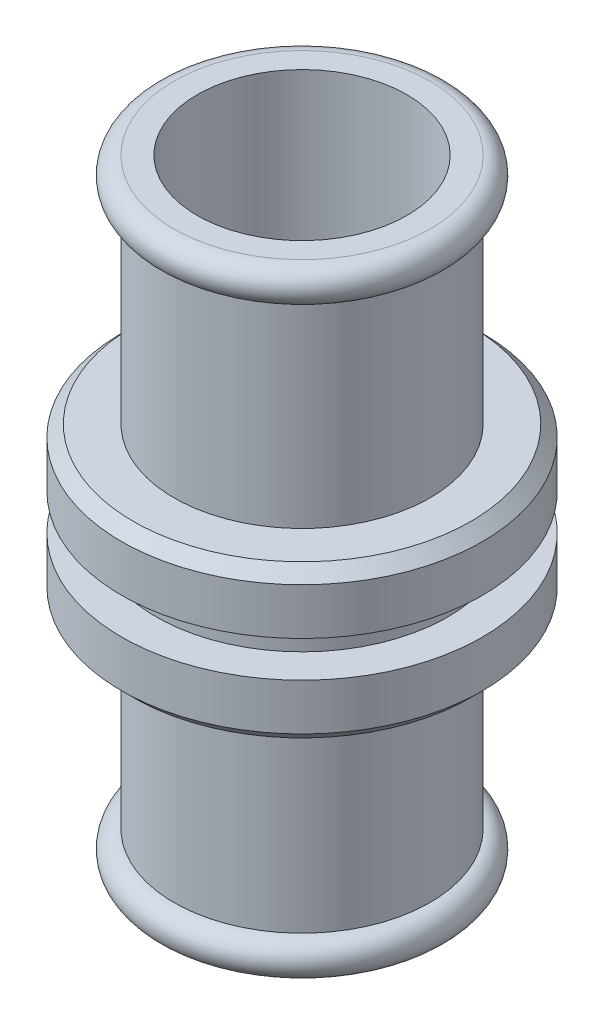
SolidWorks part; units mm, degrees
ref_plane "Alzado" through (0, 0, 0) normal (0, 0, 1) x (1, 0, 0)
ref_plane "Planta" through (0, 0, 0) normal (0, 1, 0) x (1, 0, 0)
ref_plane "Vista lateral" through (0, 0, 0) normal (1, 0, 0) x (0, 0, -1)
sketch "Croquis1" plane through (0, 0, 0) normal (0, 0, 1) x (1, 0, 0)
  line L0 (6.75, -7.5) -> (7.75, -8.5)
  line L1 (7.75, -12.5) -> (1.25, -12.5)
  line L2 (7.75, -12.5) -> (7.75, 12.5) construction
  line L3 (7.75, 12.5) -> (-7.75, 12.5) construction
  line L4 (-7.75, -12.5) -> (-7.75, 12.5) construction
  line L5 (7.75, -12.5) -> (-7.75, 12.5) construction
  line L6 (7.75, 12.5) -> (-7.75, -12.5) construction
  line L7 (1.25, -12.5) -> (7.75, -12.5)
  line L8 (-7.75, -12.5) -> (-7.75, -7.5)
  line L9 (7.75, -40.6023) -> (-7.75, -15.6023) construction
  line L10 (7.75, -12.5) -> (7.75, -8.5)
  line L11 (3.25, -7.5) -> (6.75, -7.5)
  line L12 (1.25, -12.5) -> (4.7653, -12.5)
  line L13 (-7.75, -7.5) -> (-7.75, 12.5)
  line L14 (1.25, 12.5) -> (3.25, 12.5)
  line L15 (3.25, -7.5) -> (3.25, 9.5)
  line L16 (1.25, -12.5) -> (1.25, -15.6023)
  line L17 (1.25, -14.0511) -> (4.7653, -14.0511)
  line L18 (-7.75, 12.5) -> (-7.75, -12.5)
  line L19 (-7.75, -12.5) -> (1.25, -12.5)
  line L20 (1.25, 12.5) -> (1.25, -12.5)
  line L21 (4.7653, -12.5) -> (4.7653, -15.6023)
  line L22 (7.75, -15.6023) -> (-7.75, -40.6023) construction
  line L23 (-7.75, -15.6023) -> (-7.75, -40.6023) construction
  line L24 (7.75, -40.6023) -> (-7.75, -40.6023) construction
  line L25 (7.75, -15.6023) -> (7.75, -40.6023) construction
  line L26 (1.25, -40.6023) -> (1.25, -15.6023)
  line L27 (-7.75, -15.6023) -> (1.25, -15.6023)
  line L28 (-7.75, -40.6023) -> (-7.75, -15.6023)
  line L29 (3.25, -20.6023) -> (3.25, -37.6023)
  line L30 (1.25, -40.6023) -> (3.25, -40.6023)
  line L31 (-7.75, -20.6023) -> (-7.75, -40.6023)
  line L32 (1.25, -15.6023) -> (4.7653, -15.6023)
  line L33 (3.25, -20.6023) -> (6.75, -20.6023)
  line L34 (7.75, -15.6023) -> (7.75, -19.6023)
  line L35 (-7.75, -15.6023) -> (-7.75, -20.6023)
  line L36 (1.25, -15.6023) -> (7.75, -15.6023)
  line L37 (7.75, -15.6023) -> (1.25, -15.6023)
  line L38 (6.75, -20.6023) -> (7.75, -19.6023)
  arc A0 (3.25, 12.5) -> (3.25, 9.5) centre (3.25, 11) cw
  arc A1 (3.25, -40.6023) -> (3.25, -37.6023) centre (3.25, -39.1023) ccw
  point P0 (0, 0)
  point P6 (7.75, -7.5)
  point P33 (7.75, -20.6023)
  point P34 (0, -28.1023)
  dimension "D5" = 1.5
  dimension "D1" = 15.5
  dimension "D2" = 25
  dimension "D3" = 5
  dimension "D4" = 11
  dimension "D7" = 9
revolve "Revolución1" add sketch "Croquis1" angle 360 about L13
